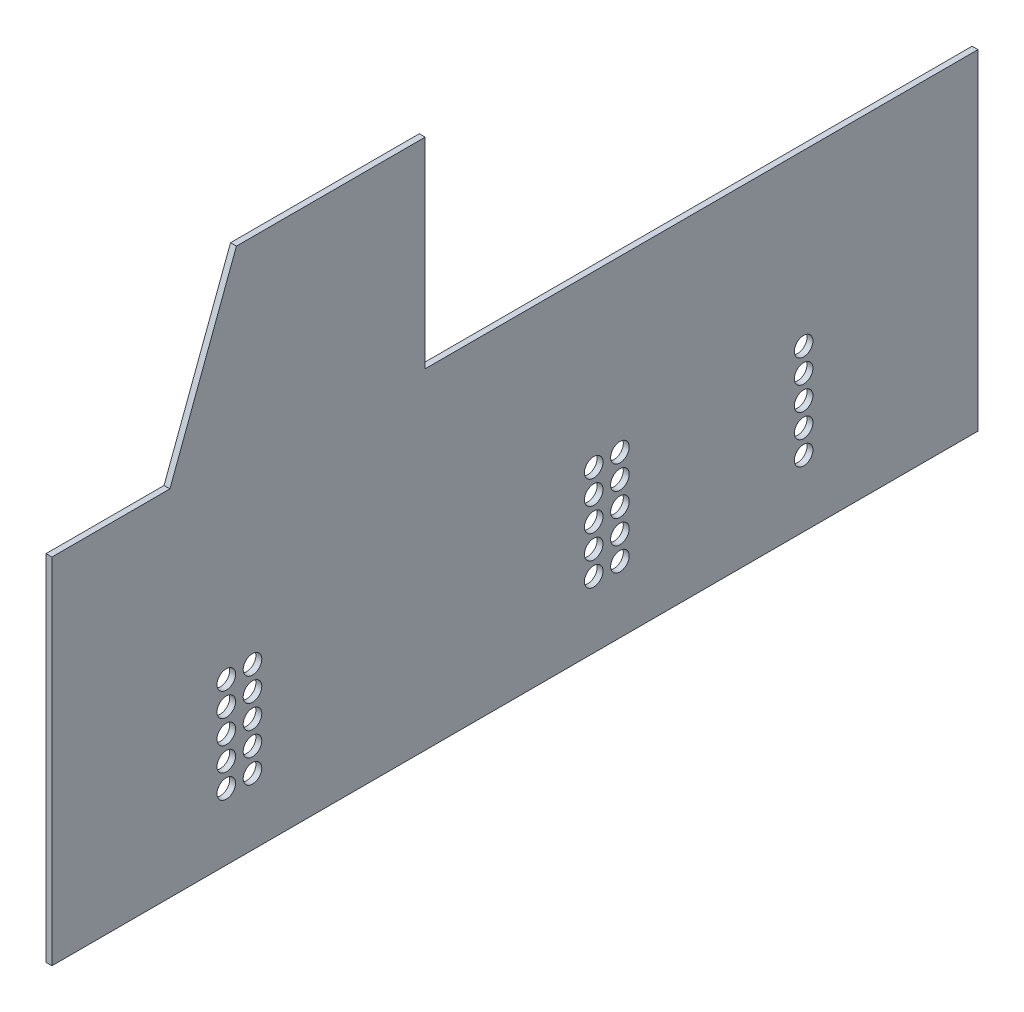
SolidWorks part; units mm, degrees
material "6061-T6 (SS)"
ref_plane "X-Y Datum" through (0, 0, 0) normal (0, 0, 1) x (1, 0, 0)
ref_plane "X-Z Datum" through (0, 0, 0) normal (0, 1, 0) x (1, 0, 0)
ref_plane "Y-Z Datum" through (0, 0, 0) normal (1, 0, 0) x (0, 0, -1)
sketch "Sketch1" plane through (0, 0, 0) normal (1, 0, 0) x (0, 0, -1)
  line L1 (-249.174, 88.9) -> (249.174, 88.9)
  line L2 (-249.174, 88.9) -> (-249.174, -88.9)
  line L3 (-249.174, -88.9) -> (249.174, -88.9)
  line L4 (249.174, 88.9) -> (249.174, -88.9)
  line L5 (-249.174, 88.9) -> (249.174, -88.9) construction
  line L6 (-249.174, -88.9) -> (249.174, 88.9) construction
  point P0 (0, 0)
  dimension "D1" = 177.8
  dimension "D2" = 498.348
extrude "Boss-Extrude1" add sketch "Sketch1" along normal mid plane 3.175
sketch "Sketch2" plane through (-1.5875, 0, 0) normal (-1, 0, 0) x (0, 0, 1)
  line L0 (48.2854, 88.9) -> (249.174, 88.9)
  line L1 (-249.174, 88.9) -> (249.174, 88.9) construction
  line L2 (249.174, 88.9) -> (249.174, 101.6)
  line L4 (48.2854, -85.725) -> (48.2854, 219.075)
  line L17 (249.174, 101.6) -> (185.674, 101.6)
  line L18 (185.674, 101.6) -> (149.8854, 196.85)
  line L19 (149.8854, 196.85) -> (48.2854, 196.85)
  line L20 (48.2854, 196.85) -> (48.2854, 88.9)
  line M14 (249.174, 88.9) -> (-249.174, 88.9)
  dimension "D1" = 12.7
  dimension "D2" = 63.5
  dimension "D3" = 107.95
  dimension "D4" = 101.6
extrude "Boss-Extrude2" add sketch "Sketch2" against normal blind 3.175 contours L18 L19 L4 L2 L17 M14
sketch "Sketch3" plane through (-1.5875, 0, 0) normal (-1, 0, 0) x (0, 0, 1)
  circle A38 centre (141.2367, -27.7749) radius 5
  circle A40 centre (155.3337, -27.7749) radius 5
extrude "Cut-Extrude3" cut sketch "Sketch3" against normal through all contours A40
pattern_linear "LPattern3" count 3 spacing 12.7 along (0, 1, 0) count 3 spacing 12.7 along (0, -1, 0) of "Cut-Extrude3"
pattern_linear "LPattern4" count 2 spacing 197.7136 along (0, 0, -1) of "LPattern3", "Cut-Extrude3"
sketch "Sketch5" plane through (-1.5875, 0, 0) normal (-1, 0, 0) x (0, 0, 1)
  circle A1 centre (155.3337, -27.7749) radius 5
  circle A2 centre (155.3337, -27.7749) radius 5
  circle A3 centre (141.2367, -27.7749) radius 5
  circle A4 centre (141.2367, -27.7749) radius 5
  dimension "D1" = 0
  dimension "D2" = 0
extrude "Cut-Extrude4" cut sketch "Sketch5" against normal through all contours A4
pattern_linear "LPattern5" count 3 spacing 12.7 along (0, 1, 0) count 3 spacing 12.7 along (0, -1, 0) of "Cut-Extrude4"
pattern_linear "LPattern6" count 4 spacing 98.8568 along (0, 0, -1) skipping (1, 0) of "LPattern5", "Cut-Extrude4"
